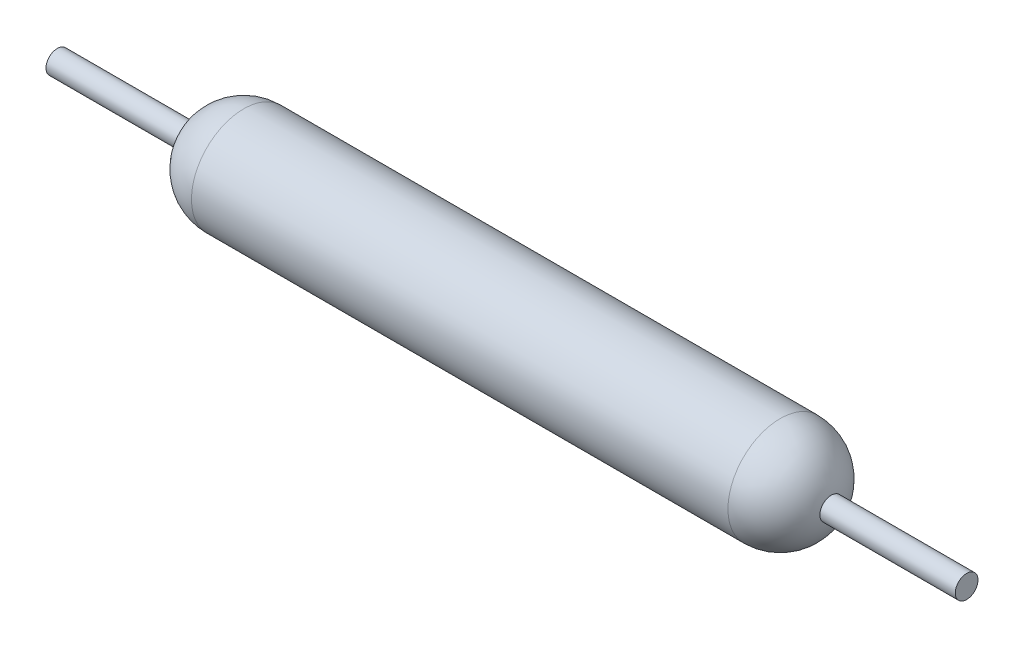
SolidWorks part; units mm, degrees
ref_plane "Front Plane" through (0, 0, 0) normal (0, 0, 1) x (1, 0, 0)
ref_plane "Top Plane" through (0, 0, 0) normal (0, 1, 0) x (1, 0, 0)
ref_plane "Right Plane" through (0, 0, 0) normal (1, 0, 0) x (0, 0, -1)
sketch "Sketch1" plane through (0, 0, 0) normal (1, 0, 0) x (0, 0, -1)
  circle A0 centre (0, 0) radius 1.15
  dimension "D1" = 2.3
extrude "Boss-Extrude1" add sketch "Sketch1" along normal blind 7.05
fillet "Fillet1" radius 1.15 1 edges at (7.05, 0, -1.15)
mirror "Mirror3" of "Boss-Extrude1", "Fillet1"
shell "Shell2" thickness 0.1
sketch "Sketch2" plane through (0, 0, 0) normal (1, 0, 0) x (0, 0, -1)
  line L1 (0.75, 0.35) -> (-0.75, 0.35)
  line L2 (0.75, 0.35) -> (0.75, 0.25)
  line L3 (0.75, 0.25) -> (-0.75, 0.25)
  line L4 (-0.75, 0.35) -> (-0.75, 0.25)
  line L5 (0.75, 0.35) -> (-0.75, 0.25) construction
  line L6 (0.75, 0.25) -> (-0.75, 0.35) construction
  point P0 (0, 0.3)
  dimension "D1" = 1.5
  dimension "D2" = 0.1
  dimension "D3" = 0.3
extrude "Boss-Extrude2" add sketch "Sketch2" against normal blind 6.1 and the other way blind 2 separate body
sketch "Sketch4" plane through (0, 0, 0) normal (1, 0, 0) x (0, 0, -1)
  line L1 (0.75, -0.25) -> (-0.75, -0.25)
  line L2 (0.75, -0.25) -> (0.75, -0.35)
  line L3 (0.75, -0.35) -> (-0.75, -0.35)
  line L4 (-0.75, -0.25) -> (-0.75, -0.35)
  line L5 (0.75, -0.25) -> (-0.75, -0.35) construction
  line L6 (0.75, -0.35) -> (-0.75, -0.25) construction
  point P0 (0, -0.3)
  dimension "D1" = 0.1
  dimension "D2" = 1.5
  dimension "D3" = 0.3
extrude "Boss-Extrude3" add sketch "Sketch4" along normal blind 6.1 and the other way blind 2 separate body
ref_plane "Plane1" through (-5, 0, 0) normal (1, 0, 0) x (0, 0, -1)
ref_plane "Plane2" through (5, 0, 0) normal (1, 0, 0) x (0, 0, -1)
sketch "Sketch5" plane through (-5, 0, 0) normal (1, 0, 0) x (0, 0, -1)
  circle A0 centre (0, 0) radius 0.25
  dimension "D1" = 0.5
extrude "Boss-Extrude4" add sketch "Sketch5" against normal blind 5
sketch "Sketch6" plane through (5, 0, 0) normal (1, 0, 0) x (0, 0, -1)
  circle A0 centre (0, 0) radius 0.25
  dimension "D1" = 0.5
extrude "Boss-Extrude5" add sketch "Sketch6" along normal blind 5
